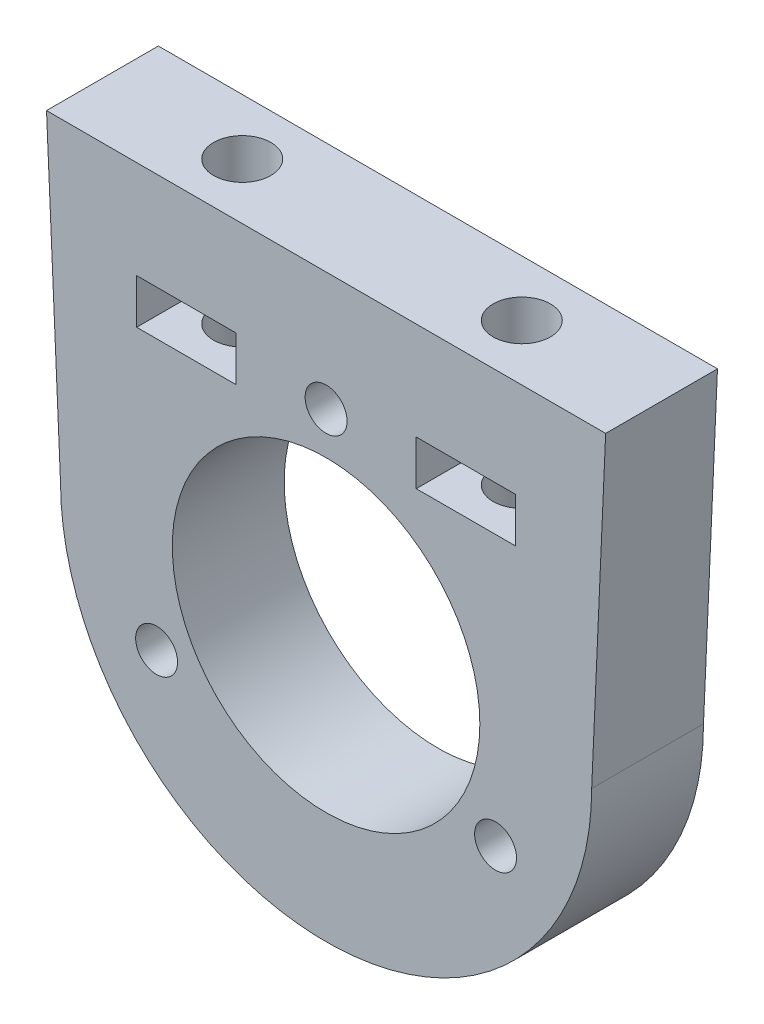
SolidWorks part; units mm, degrees
ref_plane "Front Plane" through (0, 0, 0) normal (0, 0, 1) x (1, 0, 0)
ref_plane "Top Plane" through (0, 0, 0) normal (0, 1, 0) x (1, 0, 0)
ref_plane "Right Plane" through (0, 0, 0) normal (1, 0, 0) x (0, 0, -1)
sketch "Sketch1" plane through (0, 0, 0) normal (0, 0, 1) x (1, 0, 0)
  line L0 (-19, 0) -> (-20, 22.5)
  line L1 (-20, 22.5) -> (20, 22.5)
  line L2 (20, 22.5) -> (19, 0)
  arc A0 (-19, 0) -> (19, 0) centre (0, 0) ccw
  circle A1 centre (0, 14) radius 1.5
  circle A3 centre (0, 0) radius 11
  circle A4 centre (12.1244, -7) radius 1.5
  circle A5 centre (-12.1244, -7) radius 1.5
  point P13 (0, 0)
  dimension "D1" = 38
  dimension "D2" = 3
  dimension "D3" = 22
  dimension "D4" = 14
  dimension "D6" = 40
  dimension "D7" = 20
  dimension "D8" = 22.5
  dimension "D5" = 3
extrude "Boss-Extrude1" add sketch "Sketch1" along normal blind 8
sketch "Sketch4" plane through (0, 0, 8) normal (0, 0, 1) x (1, 0, 0)
  line L0 (20, 22.5) -> (-20, 22.5) construction
  line L1 (-13.55, 15.5) -> (-6.45, 15.5)
  line L2 (-13.55, 15.5) -> (-13.55, 12.3)
  line L3 (-13.55, 12.3) -> (-6.45, 12.3)
  line L4 (-6.45, 15.5) -> (-6.45, 12.3)
  line L5 (-13.55, 15.5) -> (-6.45, 12.3) construction
  line L6 (-6.45, 15.5) -> (-13.55, 12.3) construction
  line L8 (13.55, 12.3) -> (6.45, 12.3)
  line L9 (13.55, 12.3) -> (13.55, 15.5)
  line L10 (13.55, 15.5) -> (6.45, 15.5)
  line L11 (6.45, 12.3) -> (6.45, 15.5)
  line L12 (13.55, 12.3) -> (6.45, 15.5) construction
  line L13 (13.55, 15.5) -> (6.45, 12.3) construction
  circle A0 centre (0, 14) radius 1.5 construction
  point P6 (10, 13.9)
  point P11 (-10, 13.9)
  dimension "D7" = 20
  dimension "D1" = 7.1
  dimension "D2" = 3.2
  dimension "D3" = 7
  dimension "D4" = 3.2
  dimension "D5" = 7.1
  dimension "D6" = 7
  dimension "D8" = 10
extrude "Cut-Extrude1" cut sketch "Sketch4" against normal through all
sketch "Sketch5" plane through (0, 22.5, 0) normal (0, 1, 0) x (1, 0, 0)
  line L1 (20, -8) -> (20, 0) construction
  circle A0 centre (-10, -4) radius 2.05
  circle A1 centre (10, -4) radius 2.05
  point P7 (20, -4)
  dimension "D3" = 4.1
  dimension "D1" = 20
  dimension "D2" = 10
extrude "Cut-Extrude2" cut sketch "Sketch5" against normal blind 14
equation "\"D7@Sketch1\"=\"D6@Sketch1\"/2"
equation "\"D4@Sketch4\"=\"D2@Sketch4\""
equation "\"D5@Sketch4\"=\"D1@Sketch4\""
equation "\"D6@Sketch4\"=\"D3@Sketch4\""
equation "\"D8@Sketch4\"=\"D7@Sketch4\"/2"
equation "\"D2@Sketch5\"=\"D1@Sketch5\"/2"
